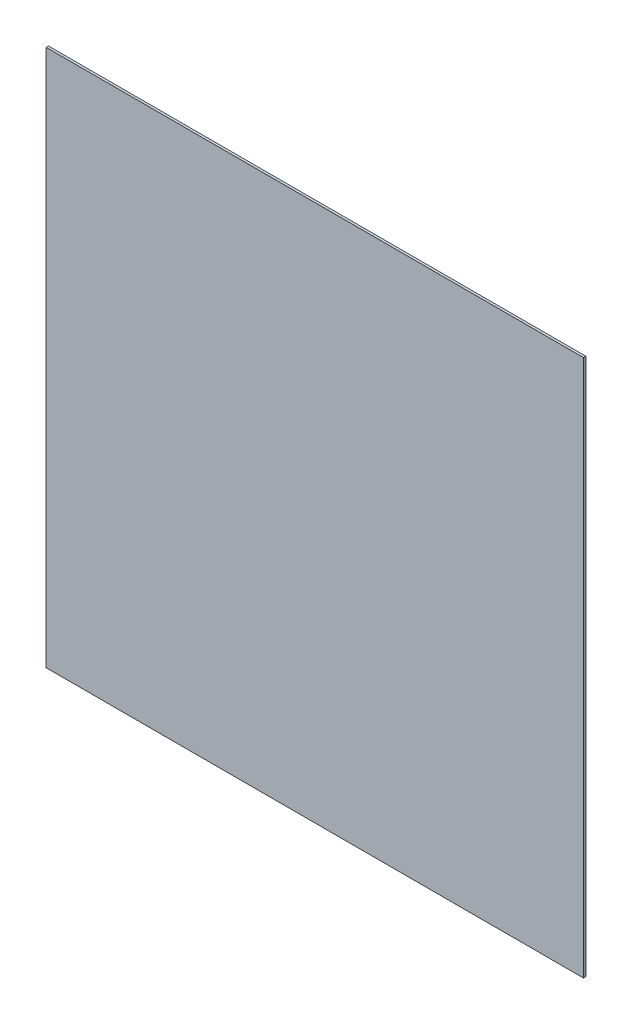
SolidWorks part; units mm, degrees
ref_plane "Front Plane" through (0, 0, 0) normal (0, 0, 1) x (1, 0, 0)
ref_plane "Top Plane" through (0, 0, 0) normal (0, 1, 0) x (1, 0, 0)
ref_plane "Right Plane" through (0, 0, 0) normal (1, 0, 0) x (0, 0, -1)
sketch "Sketch1" plane through (0, 0, 0) normal (0, 0, 1) x (1, 0, 0)
  line L1 (57.4701, -57.4701) -> (-57.4701, -57.4701)
  line L2 (57.4701, -57.4701) -> (57.4701, 57.4701)
  line L3 (57.4701, 57.4701) -> (-57.4701, 57.4701)
  line L4 (-57.4701, -57.4701) -> (-57.4701, 57.4701)
  line L5 (57.4701, -57.4701) -> (-57.4701, 57.4701) construction
  line L6 (57.4701, 57.4701) -> (-57.4701, -57.4701) construction
  point P0 (0, 0)
extrude "Boss-Extrude1" add sketch "Sketch1" along normal blind 0.508
